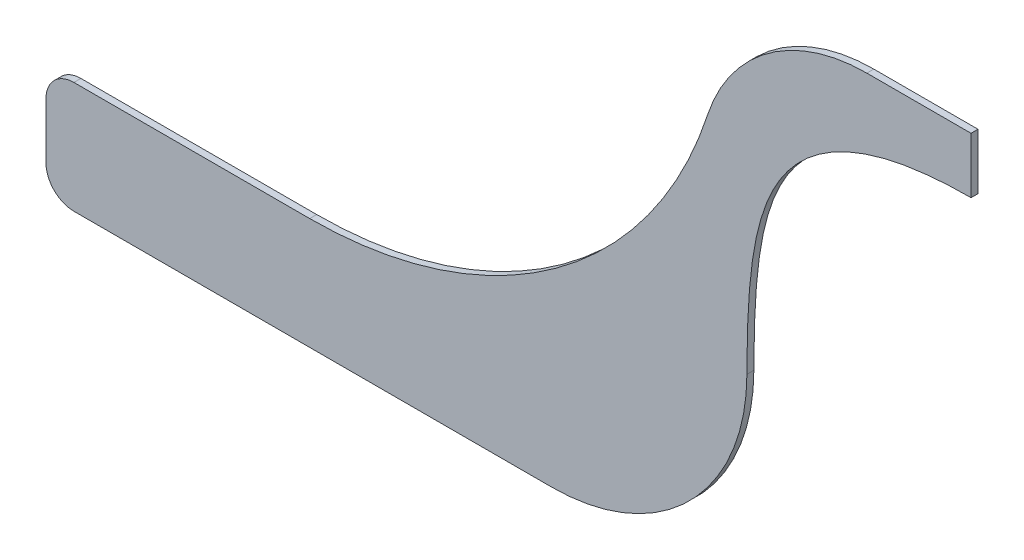
SolidWorks part; units mm, degrees
ref_plane "Front Plane" through (0, 0, 0) normal (0, 0, 1) x (1, 0, 0)
ref_plane "Top Plane" through (0, 0, 0) normal (0, 1, 0) x (1, 0, 0)
ref_plane "Right Plane" through (0, 0, 0) normal (1, 0, 0) x (0, 0, -1)
sketch "Sketch1" plane through (0, 0, 0) normal (0, 0, 1) x (1, 0, 0)
  line L7 (4.7908, -60.96) -> (439.7016, -60.96)
  line L10 (0, 0) -> (37.7775, 0) construction
  line L11 (0, 0) -> (0, 25.207) construction
  line L12 (821.5604, 358.14) -> (879.9595, 358.14) construction
  line L13 (537.7399, 133.6045) -> (531.2485, 128.3759) construction
  line L14 (532.6011, 126.4746) -> (537.7399, 133.6045) construction
  line L15 (617.5016, 116.84) -> (617.5016, 189.7402) construction
  line L16 (531.2485, 128.3759) -> (532.6011, 126.4746) construction
  line L17 (816.9226, 388.853) -> (643.6796, 348.8567) construction
  line L18 (821.5604, 358.14) -> (821.5604, 408.94)
  line L19 (821.5604, 408.94) -> (726.6915, 408.94)
  line L20 (219.4859, 40.64) -> (4.7908, 40.64)
  line L21 (-20.6092, 15.24) -> (-20.6092, -35.56)
  line L24 (617.5016, 116.84) -> (617.5016, 25.207) construction
  line L25 (537.7399, 133.6045) -> (383.6222, 21.6314) construction
  line L33 (821.5604, 358.14) -> (821.5604, 408.94)
  line L34 (821.5604, 408.94) -> (726.6915, 408.94)
  line L35 (411.4058, 7.8396) -> (183.7775, -13.2146) construction
  line L36 (207.1209, -34.079) -> (-20.7053, -15.2861) construction
  line L37 (603.425, 236.8899) -> (603.8611, 238.0136) construction
  line L38 (603.8611, 238.0136) -> (603.1798, 237.0956) construction
  line L43 (603.1798, 237.0956) -> (603.425, 236.8899) construction
  line L44 (603.3024, 236.9927) -> (521.6684, 139.7051) construction
  arc A7 (-20.6092, 15.24) -> (4.7908, 40.64) centre (4.7908, 15.24) cw
  arc A8 (-20.6092, -35.56) -> (4.7908, -60.96) centre (4.7908, -35.56) ccw
  arc A9 (439.7016, -60.96) -> (617.5016, 116.84) centre (439.7016, 116.84) ccw
  arc A23 (726.6915, 408.94) -> (581.7756, 303.7114) centre (726.6915, 256.54) ccw
  arc A24 (219.4859, 40.64) -> (581.7756, 303.7114) centre (219.4859, 421.64) ccw
  spline S1 degree 3 poles (205.7746, -34.3419) (207.4601, -34.0418) (205.7508, -34.1146) (204.3345, -34.0688) (200.8985, -34.0935) (196.6585, -34.0726) (191.0976, -34.0348) (184.5159, -33.9471) (176.9076, -33.8001) (168.395, -33.5665) (159.0697, -33.2317) (149.0451, -32.7724) (138.436, -32.1785) (127.3624, -31.4371) (115.9466, -30.55) (104.3139, -29.5199) (92.5883, -28.3721) (80.9024, -27.1095) (69.4319, -25.836) (58.3151, -24.3819) (47.6594, -22.7227) (37.4925, -20.9531) (27.8974, -19.1388) (18.9599, -17.3727) (10.7546, -15.7426) (3.3636, -14.3246) (-3.143, -13.1917) (-8.6962, -12.4233) (-13.2419, -12.045) (-16.7424, -12.1507) (-19.2577, -12.6358) (-20.8762, -14.0515) (-20.6577, -16.1973) (-19.1168, -18.2836) (-16.513, -20.7346) (-12.6851, -23.4582) (-7.6823, -26.4319) (-1.5097, -29.5261) (5.7688, -32.6504) (14.0872, -35.6766) (23.3521, -38.4968) (33.4604, -40.998) (44.2899, -43.0863) (55.7048, -44.6947) (67.5037, -45.7215) (79.5188, -46.2577) (91.6044, -46.5063) (103.6897, -46.4289) (115.6399, -46.0602) (127.3197, -45.4278) (138.5979, -44.5656) (149.3499, -43.5169) (159.4594, -42.3324) (168.8129, -41.0597) (177.3128, -39.7631) (184.8713, -38.4873) (191.384, -37.2993) (196.865, -36.2379) (201.0292, -35.3765) (204.4026, -34.6928) (205.7746, -34.3419) (207.4601, -34.0418) (205.7508, -34.1146) knots -0.012273 -0.005484 -0.001375 0 0.001366 0.005489 0.012269 0.02165 0.033497 0.04769 0.06403 0.082338 0.102396 0.123959 0.146791 0.170641 0.19524 0.220332 0.245646 0.27091 0.295825 0.31977 0.342911 0.365083 0.386049 0.405629 0.423597 0.43978 0.453966 0.466008 0.475784 0.483219 0.48846 0.492078 0.495706 0.500976 0.508553 0.518608 0.53108 0.545907 0.56292 0.581928 0.60273 0.625094 0.648778 0.673537 0.699099 0.724814 0.750772 0.776731 0.802428 0.827555 0.851851 0.875071 0.896936 0.917223 0.935694 0.952169 0.966419 0.978318 0.987727 0.994516 0.998625 1 1.001366 1.005489 1.012269 only from (207.1209, -34.079) to (207.1209, -34.079) construction
  spline S2 degree 3 poles (410.1256, 7.3468) (411.7335, 7.9351) (410.0628, 7.5665) (408.66, 7.3658) (405.2805, 6.7447) (401.1013, 6.029) (395.6183, 5.1007) (389.1213, 4.0442) (381.6031, 2.8677) (373.1792, 1.6196) (363.9375, 0.33) (353.9854, -0.9585) (343.4344, -2.2158) (332.4003, -3.4086) (321.0039, -4.5174) (309.369, -5.5229) (297.6222, -6.4286) (285.8946, -7.2144) (274.3773, -7.9522) (263.1769, -8.4505) (252.3949, -8.6669) (242.0752, -8.6896) (232.3108, -8.5691) (223.2024, -8.3817) (214.8387, -8.2013) (207.3137, -8.0883) (200.7093, -8.1024) (195.107, -8.31) (190.5647, -8.7267) (187.1357, -9.4388) (184.7428, -10.3532) (183.3948, -12.0284) (183.9825, -14.1037) (185.8624, -15.8908) (188.8522, -17.8524) (193.0949, -19.8699) (198.5381, -21.9297) (205.1542, -23.905) (212.8647, -25.7179) (221.5822, -27.2537) (231.1961, -28.4222) (241.5851, -29.1301) (252.6127, -29.3062) (264.1334, -28.908) (275.9314, -27.8704) (287.8571, -26.312) (299.8022, -24.4582) (311.6906, -22.2833) (323.3952, -19.8451) (334.7877, -17.1941) (345.7448, -14.3866) (356.1514, -11.4868) (365.9016, -8.5648) (374.892, -5.6872) (383.0376, -2.9343) (390.2598, -0.3654) (396.4672, 1.9354) (401.6806, 3.9325) (405.632, 5.5039) (408.8354, 6.763) (410.1256, 7.3468) (411.7335, 7.9351) (410.0628, 7.5665) knots -0.012273 -0.005484 -0.001375 0 0.001366 0.005489 0.012269 0.02165 0.033497 0.04769 0.06403 0.082338 0.102396 0.123959 0.146791 0.170641 0.19524 0.220332 0.245646 0.27091 0.295825 0.31977 0.342911 0.365083 0.386049 0.405629 0.423597 0.43978 0.453966 0.466008 0.475784 0.483219 0.48846 0.492078 0.495706 0.500976 0.508553 0.518608 0.53108 0.545907 0.56292 0.581928 0.60273 0.625094 0.648778 0.673537 0.699099 0.724814 0.750772 0.776731 0.802428 0.827555 0.851851 0.875071 0.896936 0.917223 0.935694 0.952169 0.966419 0.978318 0.987727 0.994516 0.998625 1 1.001366 1.005489 1.012269 only from (411.4058, 7.8396) to (411.4058, 7.8396) construction
  spline S3 degree 3 poles (531.2485, 128.3759) (529.7206, 127.1452) (528.1914, 125.9161) (525.1247, 123.4682) (523.588, 122.2484) (518.9672, 118.6029) (515.8721, 116.1904) (506.5465, 109.0148) (500.2726, 104.3143) (487.609, 95.0831) (481.2187, 90.5532) (468.3373, 81.6412) (461.846, 77.2593) (452.0631, 70.7538) (448.7931, 68.5987) (443.8873, 65.3669) (442.2514, 64.2907) (438.9645, 62.1602) (437.313, 61.1067) (432.3377, 57.977) (428.993, 55.9311) (422.2638, 51.8981) (418.879, 49.9111) (412.0945, 45.959) (408.6946, 43.9953) (403.6168, 41.0142) (401.928, 40.0143) (398.5687, 37.9847) (396.8979, 36.9557) (393.5939, 34.8367) (391.9596, 33.7486) (389.571, 32.0144) (388.7836, 31.4182) (387.2581, 30.1765) (386.5172, 29.5325) (385.4728, 28.4961) (385.1355, 28.1393) (384.4948, 27.3898) (384.1901, 26.9933) (383.6477, 26.1633) (383.4103, 25.7298) (383.1457, 25.0291) (383.0736, 24.7888) (382.9704, 24.304) (382.9387, 24.0579) (382.9256, 23.5565) (382.9452, 23.3073) (383.0394, 22.8216) (383.1144, 22.5809) (383.3112, 22.1218) (383.4316, 21.9051) (383.7147, 21.4961) (383.879, 21.3034) (384.2326, 20.9546) (384.4233, 20.7961) (384.8271, 20.5052) (385.0408, 20.3724) (385.6951, 20.0154) (386.1542, 19.8292) (387.1007, 19.5203) (387.5843, 19.3991) (388.5564, 19.2065) (389.0466, 19.1339) (390.0331, 19.0223) (390.5299, 18.984) (391.5187, 18.9348) (392.0121, 18.9233) (393.4899, 18.9207) (394.4717, 18.9615) (396.431, 19.1021) (397.4082, 19.2028) (399.3591, 19.4513) (400.3327, 19.5995) (402.2768, 19.9365) (403.2473, 20.1253) (406.138, 20.7418) (408.0434, 21.2198) (413.7065, 22.818) (417.4116, 24.1008) (422.8837, 26.2897) (424.6959, 27.0653) (428.2804, 28.6954) (430.0482, 29.5478) (435.2838, 32.2084) (438.6839, 34.1201) (445.322, 38.191) (448.5602, 40.3499) (454.8861, 44.8975) (457.9674, 47.2959) (462.5391, 50.9704) (464.053, 52.2105) (467.06, 54.7224) (468.5523, 55.9931) (475.9447, 62.401) (481.6548, 67.7138) (492.7274, 78.6576) (498.0893, 84.2891) (508.4939, 95.8441) (513.5362, 101.7682) (520.8641, 110.8696) (523.2672, 113.9397) (526.8124, 118.5991) (527.9841, 120.1614) (530.3075, 123.3044) (531.457, 124.8871) (532.6011, 126.4746) knots 0 0 0 0 0.015625 0.015625 0.03125 0.03125 0.0625 0.0625 0.125 0.125 0.1875 0.1875 0.25 0.25 0.28125 0.28125 0.296875 0.296875 0.3125 0.3125 0.34375 0.34375 0.375 0.375 0.40625 0.40625 0.421875 0.421875 0.4375 0.4375 0.453125 0.453125 0.460938 0.460938 0.46875 0.46875 0.472656 0.472656 0.476563 0.476563 0.480469 0.480469 0.482422 0.482422 0.484375 0.484375 0.486328 0.486328 0.488281 0.488281 0.490234 0.490234 0.492188 0.492188 0.494141 0.494141 0.496094 0.496094 0.5 0.5 0.503906 0.503906 0.507813 0.507813 0.511719 0.511719 0.515625 0.515625 0.523438 0.523438 0.53125 0.53125 0.539063 0.539063 0.546875 0.546875 0.5625 0.5625 0.59375 0.59375 0.609375 0.609375 0.625 0.625 0.65625 0.65625 0.6875 0.6875 0.71875 0.71875 0.734375 0.734375 0.75 0.75 0.8125 0.8125 0.875 0.875 0.9375 0.9375 0.96875 0.96875 0.984375 0.984375 1 1 1 1 construction
  spline S5 degree 3 poles (617.5016, 116.84) (617.5016, 198.1033) (630.4129, 310.6768) (736.5759, 358.14) (821.5604, 358.14) knots 0 0 0 0 0.504521 1 1 1 1
  spline S6 degree 3 poles (205.7746, -34.3419) (207.4601, -34.0418) (205.7508, -34.1146) (204.3345, -34.0688) (200.8985, -34.0935) (196.6585, -34.0726) (191.0976, -34.0348) (184.5159, -33.9471) (176.9076, -33.8001) (168.395, -33.5665) (159.0697, -33.2317) (149.0451, -32.7724) (138.436, -32.1785) (127.3624, -31.4371) (115.9466, -30.55) (104.3139, -29.5199) (92.5883, -28.3721) (80.9024, -27.1095) (69.4319, -25.836) (58.3151, -24.3819) (47.6594, -22.7227) (37.4925, -20.9531) (27.8974, -19.1388) (18.9599, -17.3727) (10.7546, -15.7426) (3.3636, -14.3246) (-3.143, -13.1917) (-8.6962, -12.4233) (-13.2419, -12.045) (-16.7424, -12.1507) (-19.2577, -12.6358) (-20.8762, -14.0515) (-20.6577, -16.1973) (-19.1168, -18.2836) (-16.513, -20.7346) (-12.6851, -23.4582) (-7.6823, -26.4319) (-1.5097, -29.5261) (5.7688, -32.6504) (14.0872, -35.6766) (23.3521, -38.4968) (33.4604, -40.998) (44.2899, -43.0863) (55.7048, -44.6947) (67.5037, -45.7215) (79.5188, -46.2577) (91.6044, -46.5063) (103.6897, -46.4289) (115.6399, -46.0602) (127.3197, -45.4278) (138.5979, -44.5656) (149.3499, -43.5169) (159.4594, -42.3324) (168.8129, -41.0597) (177.3128, -39.7631) (184.8713, -38.4873) (191.384, -37.2993) (196.865, -36.2379) (201.0292, -35.3765) (204.4026, -34.6928) (205.7746, -34.3419) (207.4601, -34.0418) (205.7508, -34.1146) knots -0.012273 -0.005484 -0.001375 0 0.001366 0.005489 0.012269 0.02165 0.033497 0.04769 0.06403 0.082338 0.102396 0.123959 0.146791 0.170641 0.19524 0.220332 0.245646 0.27091 0.295825 0.31977 0.342911 0.365083 0.386049 0.405629 0.423597 0.43978 0.453966 0.466008 0.475784 0.483219 0.48846 0.492078 0.495706 0.500976 0.508553 0.518608 0.53108 0.545907 0.56292 0.581928 0.60273 0.625094 0.648778 0.673537 0.699099 0.724814 0.750772 0.776731 0.802428 0.827555 0.851851 0.875071 0.896936 0.917223 0.935694 0.952169 0.966419 0.978318 0.987727 0.994516 0.998625 1 1.001366 1.005489 1.012269 only from (207.1209, -34.079) to (207.1209, -34.079) construction
  spline S7 degree 3 poles (603.1798, 237.0956) (603.1409, 237.0431) (602.9853, 236.8334) (602.6357, 236.3634) (602.0551, 235.5834) (601.2454, 234.4997) (600.2104, 233.1201) (598.9544, 231.4547) (597.4824, 229.5162) (595.8009, 227.3185) (593.9169, 224.8782) (591.8387, 222.2129) (589.575, 219.3427) (587.1364, 216.2879) (584.5343, 213.0706) (581.7817, 209.713) (578.8924, 206.2385) (575.8828, 202.6698) (572.77, 199.0301) (569.5733, 195.3419) (566.3136, 191.6266) (563.0126, 187.9061) (559.6953, 184.1993) (556.3835, 180.528) (553.1121, 176.9007) (549.84, 173.3942) (546.6014, 170.018) (543.4269, 166.7835) (540.349, 163.6997) (537.3998, 160.7746) (534.6111, 158.0147) (532.0131, 155.426) (529.6348, 153.0132) (527.5024, 150.7813) (525.6402, 148.7341) (524.069, 146.8754) (522.8063, 145.2082) (521.8652, 143.7336) (521.2551, 142.448) (520.9798, 141.3371) (521.0894, 140.3657) (521.655, 139.6233) (522.5649, 139.18) (523.7583, 139.0042) (525.2335, 139.0722) (526.9899, 139.385) (529.0158, 139.9473) (531.2916, 140.7664) (533.793, 141.8474) (536.4921, 143.1961) (539.3588, 144.8158) (542.3616, 146.7091) (545.4677, 148.8765) (548.6451, 151.3156) (551.8616, 154.0221) (555.0866, 156.9882) (558.291, 160.2034) (561.4475, 163.6541) (564.5321, 167.3227) (567.5175, 171.1898) (570.4578, 175.1744) (573.3277, 179.2579) (576.1155, 183.4101) (578.8075, 187.6023) (581.3928, 191.8041) (583.8604, 195.9854) (586.2013, 200.1152) (588.4078, 204.1624) (590.473, 208.0964) (592.3918, 211.8867) (594.1595, 215.5037) (595.7733, 218.9185) (597.2316, 222.1031) (598.5327, 225.0316) (599.677, 227.679) (600.6649, 230.0229) (601.4974, 232.0427) (602.1759, 233.7207) (602.7018, 235.0418) (603.0761, 235.9942) (603.3005, 236.5691) (603.4001, 236.8256) (603.425, 236.8899) knots 0 0 0 0 0.000751 0.002998 0.006728 0.011917 0.018533 0.026535 0.035872 0.046487 0.058313 0.071277 0.085299 0.100293 0.116166 0.13282 0.150153 0.16806 0.186431 0.205154 0.224112 0.243191 0.262273 0.281239 0.299973 0.318368 0.336314 0.3537 0.370414 0.38635 0.401402 0.415472 0.428469 0.440308 0.45092 0.460246 0.46825 0.474922 0.480304 0.484529 0.48793 0.491137 0.494783 0.499272 0.504867 0.511675 0.51972 0.528986 0.53943 0.550997 0.56362 0.577229 0.591748 0.607102 0.623214 0.640008 0.657405 0.675329 0.693699 0.712432 0.731423 0.750565 0.769746 0.788854 0.807777 0.826399 0.844608 0.86229 0.879335 0.895632 0.911077 0.925567 0.939006 0.951301 0.962367 0.972127 0.980511 0.987456 0.992913 0.99684 0.999209 1 1 1 1 construction
  spline S10 degree 3 poles (816.9226, 388.853) (814.991, 389.1617) (813.049, 389.418) (808.9639, 389.9173) (806.8198, 390.1508) (802.5312, 390.5834) (800.3856, 390.7814) (793.9457, 391.3346) (789.6486, 391.6496) (781.0476, 392.1883) (776.7437, 392.4104) (768.1285, 392.7547) (763.8218, 392.8766) (755.2201, 392.9906) (750.9239, 392.9821) (742.3433, 392.798) (738.0588, 392.6232) (729.5085, 392.009) (725.2435, 391.5592) (716.7379, 390.3128) (712.4972, 389.519) (707.2126, 388.295) (706.1553, 388.0382) (704.0497, 387.503) (703.0014, 387.2245) (699.8702, 386.3562) (697.8008, 385.7336) (691.648, 383.7326) (687.6203, 382.2199) (679.7164, 378.8296) (675.8381, 376.9571) (670.1509, 373.8341) (668.2772, 372.7401) (664.5811, 370.4285) (662.7734, 369.2205) (659.2586, 366.6881) (657.5502, 365.3633) (654.2541, 362.5693) (652.6655, 361.1013) (650.404, 358.7539) (649.6704, 357.9473) (648.2535, 356.2739) (647.5744, 355.412) (646.2982, 353.6423) (645.7, 352.7322) (644.6035, 350.849) (644.1056, 349.8755) (643.6796, 348.8567) knots 0.548291 0.548291 0.548291 0.548291 0.5625 0.5625 0.578125 0.578125 0.59375 0.59375 0.625 0.625 0.65625 0.65625 0.6875 0.6875 0.71875 0.71875 0.75 0.75 0.78125 0.78125 0.8125 0.8125 0.820313 0.820313 0.828125 0.828125 0.84375 0.84375 0.875 0.875 0.90625 0.90625 0.921875 0.921875 0.9375 0.9375 0.953125 0.953125 0.96875 0.96875 0.976563 0.976563 0.984375 0.984375 0.992188 0.992188 1 1 1 1 construction
  spline S11 degree 3 poles (643.6796, 348.8567) (643.653, 348.7878) (643.6253, 348.715) (643.5722, 348.573) (643.4935, 348.3598) (643.4183, 348.1456) (643.2727, 347.7158) (643.182, 347.4276) (642.9315, 346.5569) (642.7929, 345.9686) (642.5851, 344.773) (642.5174, 344.1695) (642.4755, 342.9658) (642.4977, 342.3633) (642.6745, 341.1565) (642.831, 340.5709) (643.1405, 339.8763) (643.2084, 339.7385) (643.3581, 339.4732) (643.44, 339.3455) (643.6158, 339.0987) (643.7092, 338.9792) (643.9182, 338.756) (644.0316, 338.651) (644.2733, 338.4686) (644.403, 338.3908) (644.674, 338.2527) (644.815, 338.1907) (645.2425, 338.0332) (645.5366, 337.963) (646.1329, 337.8537) (646.4363, 337.8189) (647.0412, 337.7754) (647.3441, 337.7663) (647.9508, 337.7701) (648.2558, 337.7832) (648.8565, 337.8272) (649.1531, 337.858) (650.0343, 337.9708) (650.6107, 338.0726) (652.3227, 338.4183) (653.4392, 338.7075) (656.7414, 339.688) (658.8823, 340.4857) (663.1129, 342.2024) (665.2004, 343.1269) (669.3454, 345.0468) (671.4027, 346.0429) (675.5077, 348.0581) (677.5553, 349.077) (681.6557, 351.1031) (683.7092, 352.1082) (689.8891, 355.0775) (694.0342, 356.9973) (700.3018, 359.7582) (702.3992, 360.6593) (706.6117, 362.4188) (708.7278, 363.2774) (715.0969, 365.7769) (719.374, 367.3389) (727.9864, 370.2662) (732.3221, 371.6302) (741.0367, 374.2128) (745.4151, 375.4331) (754.2089, 377.7487) (758.6242, 378.8444) (767.4925, 380.9084) (771.949, 381.8775) (780.8821, 383.6634) (785.3596, 384.4808) (794.3365, 385.9658) (798.8355, 386.6354) (807.8527, 387.8437) (812.3709, 388.3814) (816.907, 388.8513) (816.9148, 388.8521) (816.9226, 388.853) knots 0 0 0 0 0.000488 0.000488 0.000977 0.001953 0.001953 0.003906 0.003906 0.007812 0.007812 0.011719 0.011719 0.015625 0.015625 0.019531 0.019531 0.020508 0.020508 0.021484 0.021484 0.022461 0.022461 0.023438 0.023438 0.024414 0.024414 0.025391 0.025391 0.027344 0.027344 0.029297 0.029297 0.03125 0.03125 0.033203 0.033203 0.035156 0.035156 0.039063 0.039063 0.046875 0.046875 0.0625 0.0625 0.078125 0.078125 0.09375 0.09375 0.109375 0.109375 0.125 0.125 0.15625 0.15625 0.171875 0.171875 0.1875 0.1875 0.21875 0.21875 0.25 0.25 0.28125 0.28125 0.3125 0.3125 0.34375 0.34375 0.375 0.375 0.40625 0.40625 0.4375 0.4375 0.437554 0.437554 0.437554 0.437554 construction
  point P7 (614.9931, 189.7402)
  point P11 (617.5016, 116.84)
  point P18 (207.1209, -34.079)
  dimension "D3" = 20.6092
  dimension "D5" = 25.4
  dimension "D6" = 25.4
  dimension "D7" = 381
  dimension "D8" = 152.4
  dimension "D11" = 214.6951
  dimension "D12" = 101.6
  dimension "D14" = 177.8
  dimension "D9" = 469.9
  dimension "D4" = 60.96
  dimension "D10" = 50.8
  dimension "D17" = 842.1696
  dimension "D22" = 90
  dimension "D23" = 90
extrude "Boss-Extrude1" add sketch "Sketch1" along normal blind 6.35
